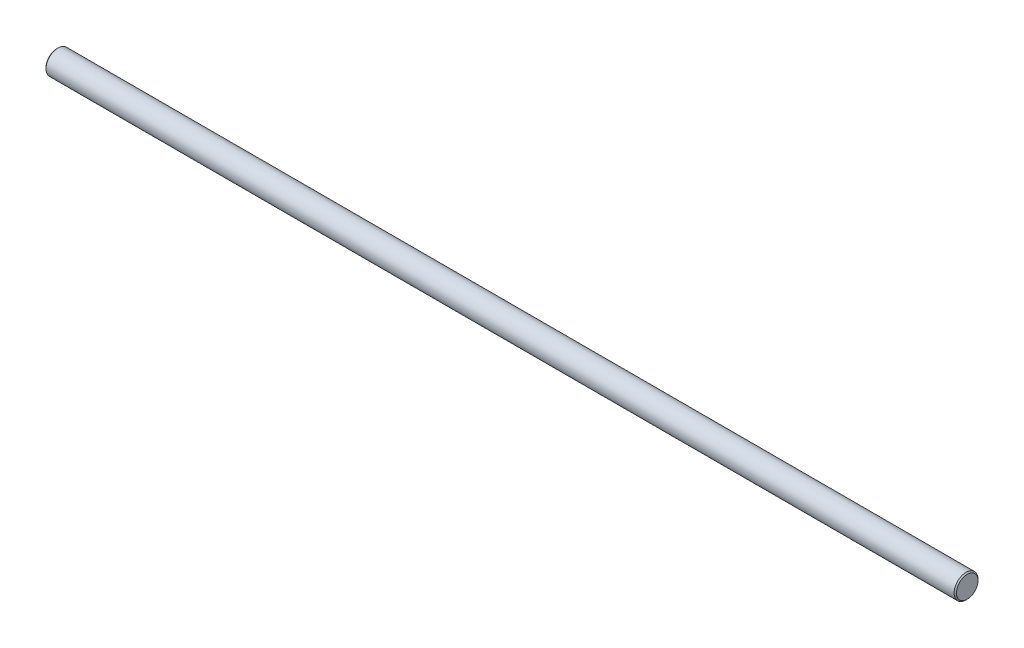
SolidWorks part; units mm, degrees
ref_plane "Front Plane" through (0, 0, 0) normal (0, 0, 1) x (1, 0, 0)
ref_plane "Top Plane" through (0, 0, 0) normal (0, 1, 0) x (1, 0, 0)
ref_plane "Right Plane" through (0, 0, 0) normal (1, 0, 0) x (0, 0, -1)
ref_plane "Plane1" through (0, 0, 0) normal (0, 0, 1) x (1, 0, 0)
sketch "Sketch1" plane through (0, 0, 0) normal (0, 0, 1) x (1, 0, 0)
  line L0 (0, 0) -> (0, 4.5)
  line L1 (0, 4.5) -> (0.5, 5)
  line L2 (0.5, 5) -> (379.5, 5)
  line L3 (379.5, 5) -> (380, 4.5)
  line L4 (380, 4.5) -> (380, 0)
  line L5 (380, 0) -> (0, 0)
  line L6 (380, 0) -> (0, 0) construction
revolve "Revolve1" add sketch "Sketch1" angle 360 about L6
